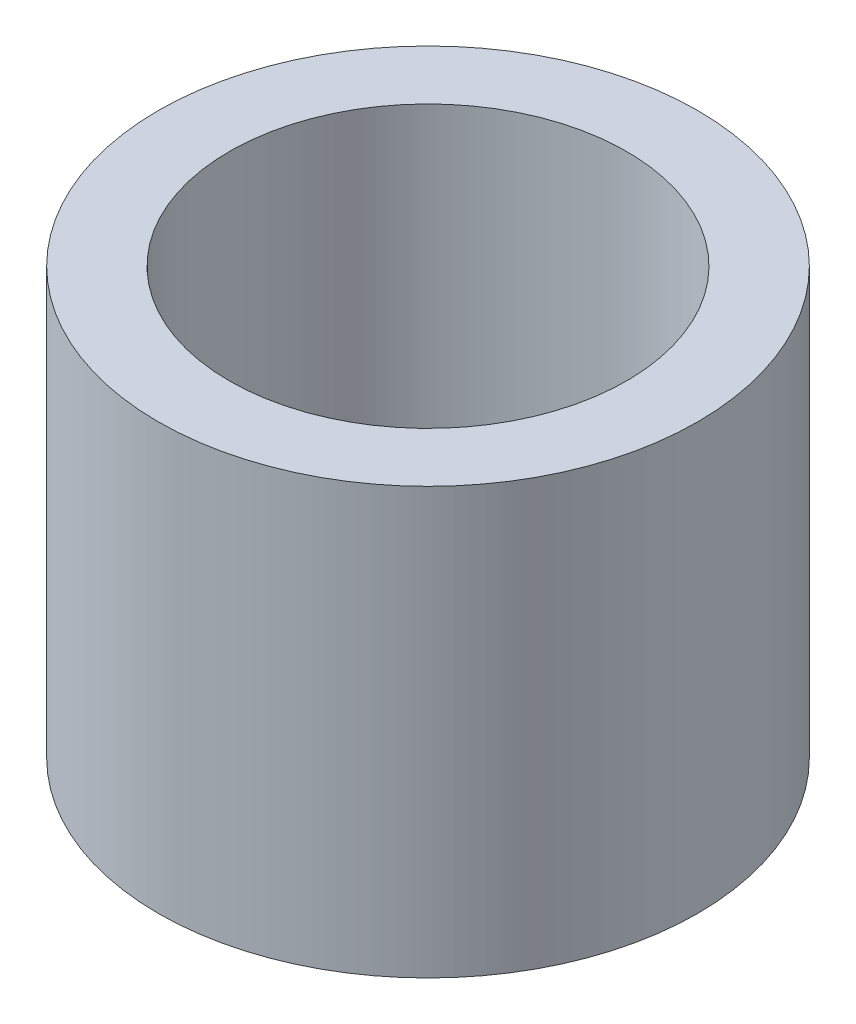
SolidWorks part; units mm, degrees
ref_plane "Front Plane" through (0, 0, 0) normal (0, 0, 1) x (1, 0, 0)
ref_plane "Top Plane" through (0, 0, 0) normal (0, 1, 0) x (1, 0, 0)
ref_plane "Right Plane" through (0, 0, 0) normal (1, 0, 0) x (0, 0, -1)
sketch "Sketch2" plane through (0, 0, 0) normal (0, 1, 0) x (1, 0, 0)
  circle A0 centre (0, 0) radius 4.75
  circle A1 centre (0, 0) radius 3.5
  dimension "D1" = 9.5
  dimension "D2" = 7
extrude "Boss-Extrude1" add sketch "Sketch2" along normal mid plane 7.5
